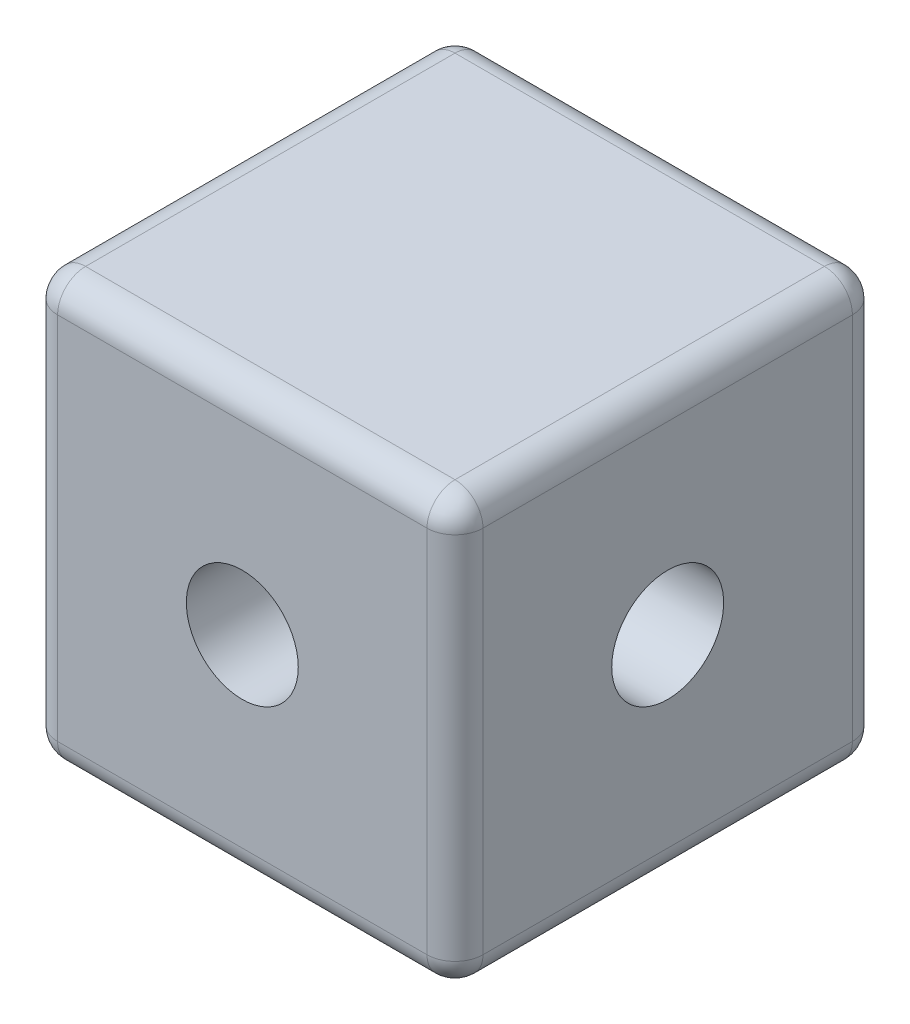
SolidWorks part; units mm, degrees
ref_plane "Front Plane" through (0, 0, 0) normal (0, 0, 1) x (1, 0, 0)
ref_plane "Top Plane" through (0, 0, 0) normal (0, 1, 0) x (1, 0, 0)
ref_plane "Right Plane" through (0, 0, 0) normal (1, 0, 0) x (0, 0, -1)
sketch "Sketch2" plane through (0, 0, 0) normal (0, 1, 0) x (1, 0, 0)
  line L1 (-3.8, -3.8) -> (3.8, -3.8)
  line L2 (-3.8, -3.8) -> (-3.8, 3.8)
  line L3 (-3.8, 3.8) -> (3.8, 3.8)
  line L4 (3.8, -3.8) -> (3.8, 3.8)
  line L5 (-3.8, -3.8) -> (3.8, 3.8) construction
  line L6 (-3.8, 3.8) -> (3.8, -3.8) construction
  point P0 (0, 0)
  dimension "D1" = 7.6
  dimension "D2" = 7.6
extrude "Boss-Extrude1" add sketch "Sketch2" along normal blind 7.6
fillet "Fillet1" radius 0.5 12 edges at (3.8, 0, 0) (-3.8, 0, 0) (3.8, 3.8, -3.8) (-3.8, 3.8, -3.8) (0, 0, -3.8) (-3.8, 7.6, 0) (0, 7.6, -3.8) (3.8, 7.6, 0) (-3.8, 3.8, 3.8) (0, 7.6, 3.8) (3.8, 3.8, 3.8) (0, 0, 3.8)
sketch "Sketch3" plane through (-3.8, 0, 0) normal (-1, 0, 0) x (0, 0, 1)
  line L0 (-3.8, 3.8) -> (3.3, 3.8) construction
  line L1 (-3.8, 0.5) -> (-3.8, 7.1) construction
  line L2 (3.3, 0.5) -> (3.3, 7.1) construction
  circle A0 centre (0, 3.8) radius 1
  dimension "D1" = 2
extrude "Cut-Extrude1" cut sketch "Sketch3" against normal blind 10
sketch "Sketch4" plane through (0, 0, 3.8) normal (0, 0, 1) x (1, 0, 0)
  line L0 (-3.8, 3.8) -> (3.8, 3.8) construction
  line L1 (-3.8, 0.5) -> (-3.8, 7.1) construction
  line L2 (3.8, 7.1) -> (3.8, 0.5) construction
  circle A0 centre (0, 3.8) radius 1
  dimension "D1" = 2
extrude "Cut-Extrude2" cut sketch "Sketch4" against normal up to surface (7.6 mm away) up to face at (0, 3.8, -3.8)
